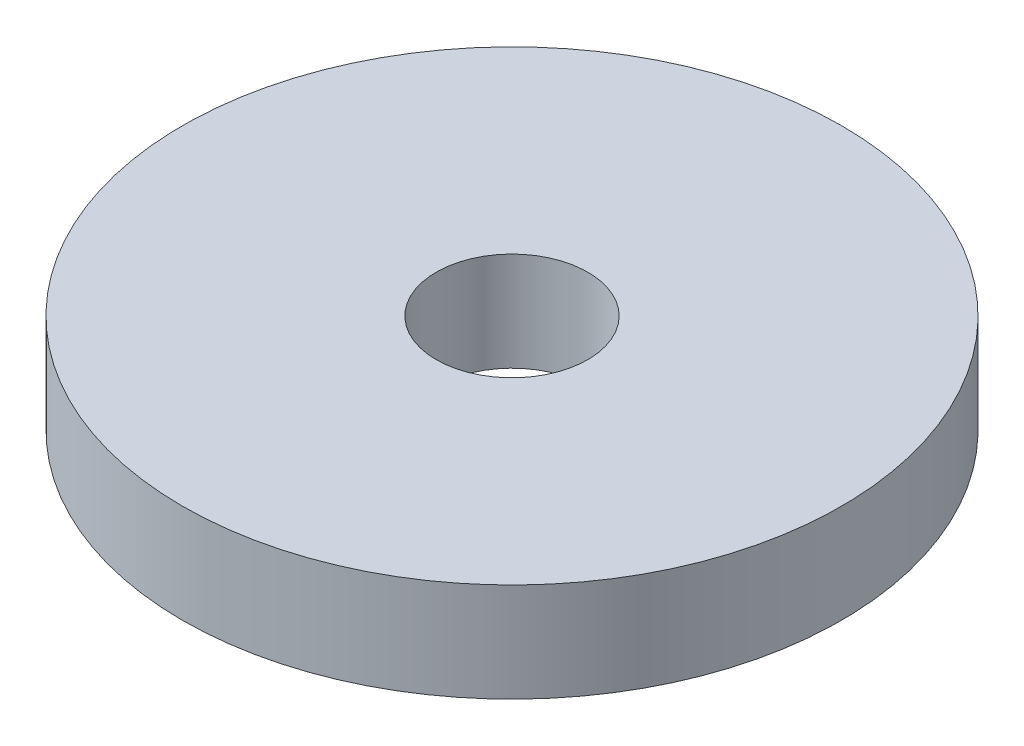
SolidWorks part; units mm, degrees
ref_plane "Front Plane" through (0, 0, 0) normal (0, 0, 1) x (1, 0, 0)
ref_plane "Top Plane" through (0, 0, 0) normal (0, 1, 0) x (1, 0, 0)
ref_plane "Right Plane" through (0, 0, 0) normal (1, 0, 0) x (0, 0, -1)
sketch "Sketch1" plane through (0, 0, 0) normal (0, 1, 0) x (1, 0, 0)
  circle A0 centre (0, 0) radius 2.3
  circle A4 centre (0, 0) radius 10
  dimension "D1" = 4.6
  dimension "D2" = 10
extrude "Boss-Extrude1" add sketch "Sketch1" along normal blind 3
